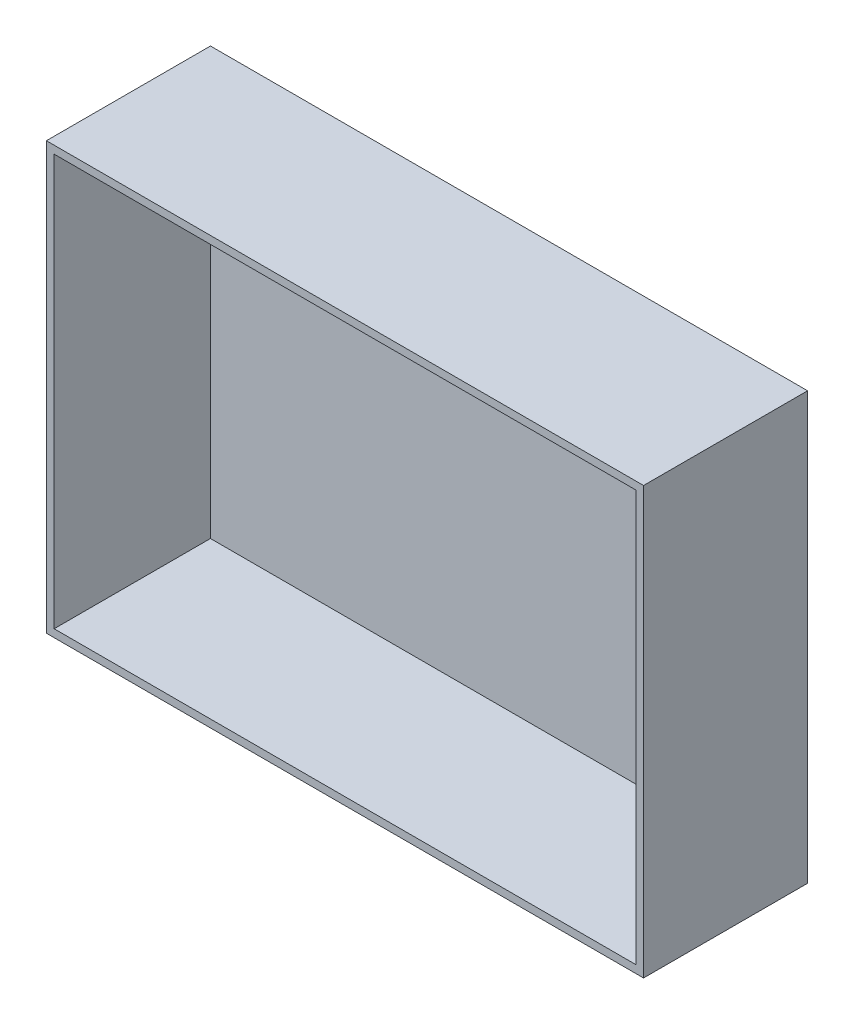
SolidWorks part; units mm, degrees
ref_plane "Front Plane" through (0, 0, 0) normal (0, 0, 1) x (1, 0, 0)
ref_plane "Top Plane" through (0, 0, 0) normal (0, 1, 0) x (1, 0, 0)
ref_plane "Right Plane" through (0, 0, 0) normal (1, 0, 0) x (0, 0, -1)
sketch "Sketch1" plane through (0, 0, 0) normal (0, 0, 1) x (1, 0, 0)
  line L1 (0, 0) -> (231.14, 0)
  line L2 (0, 0) -> (0, 165.1)
  line L3 (0, 165.1) -> (231.14, 165.1)
  line L4 (231.14, 0) -> (231.14, 165.1)
  dimension "D1" = 231.14
  dimension "D2" = 165.1
extrude "Boss-Extrude1" add sketch "Sketch1" along normal blind 63.5
sketch "Sketch2" plane through (0, 0, 63.5) normal (0, 0, 1) x (1, 0, 0)
  line L0 (3, 162.1) -> (3, 3)
  line L1 (0, 165.1) -> (231.14, 165.1)
  line L2 (0, 165.1) -> (0, 0)
  line L3 (0, 0) -> (231.14, 0)
  line L4 (231.14, 165.1) -> (231.14, 0)
  line L5 (3, 3) -> (228.14, 3)
  line L6 (228.14, 162.1) -> (228.14, 3)
  line L7 (3, 162.1) -> (228.14, 162.1)
  dimension "D1" = 3
extrude "Cut-Extrude1" cut sketch "Sketch2" against normal offset from surface (60.5 mm away) 3 flip side to cut up to face at (115.57, 82.55, 0)
ref_plane "Plane1" through (0, 82.55, 0) normal (0, -1, 0) x (-1, 0, 0)
